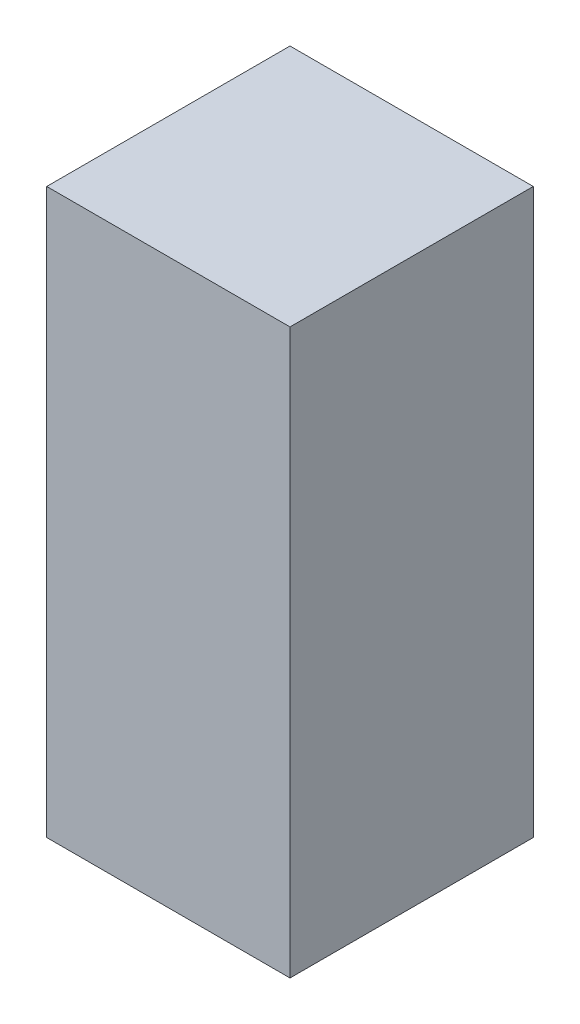
SolidWorks part; units mm, degrees
material "Custom Plastic"
ref_plane "X-Y Datum" through (0, 0, 0) normal (0, 0, 1) x (1, 0, 0)
ref_plane "X-Z Datum" through (0, 0, 0) normal (0, 1, 0) x (1, 0, 0)
ref_plane "Y-Z Datum" through (0, 0, 0) normal (1, 0, 0) x (0, 0, -1)
sketch "Sketch1" plane through (0, 0, 0) normal (0, 1, 0) x (1, 0, 0)
  line L1 (0, 0) -> (38.354, 0)
  line L2 (0, 0) -> (0, 38.354)
  line L3 (0, 38.354) -> (38.354, 38.354)
  line L4 (38.354, 0) -> (38.354, 38.354)
  dimension "D1" = 38.354
  dimension "D2" = 38.354
extrude "Boss-Extrude1" add sketch "Sketch1" along normal blind 88.9
